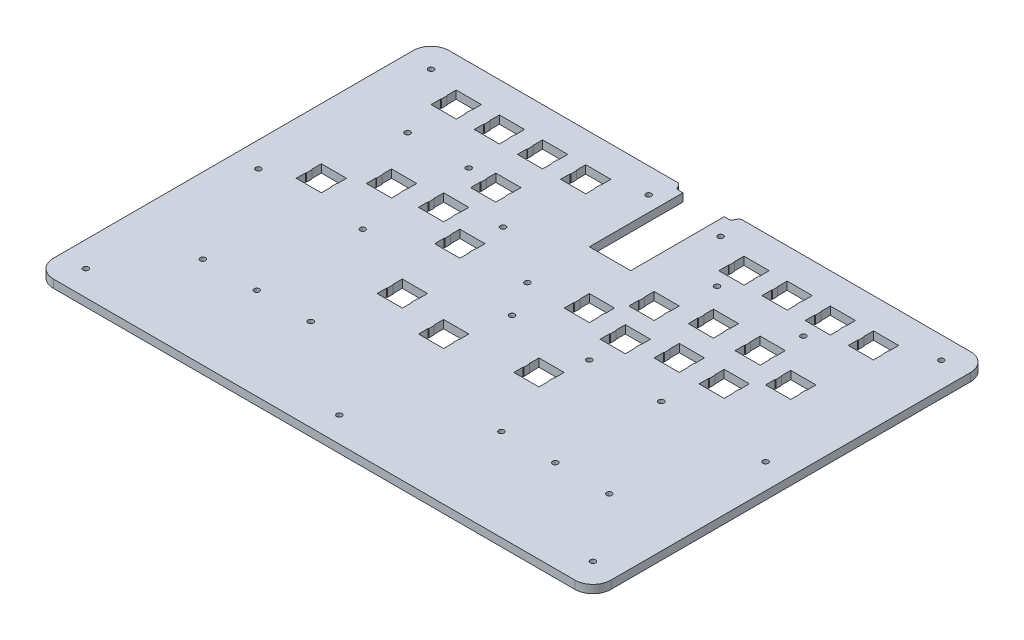
SolidWorks part; units mm, degrees
ref_plane "前视基准面" through (0, 0, 0) normal (0, 0, 1) x (1, 0, 0)
ref_plane "上视基准面" through (0, 0, 0) normal (0, 1, 0) x (1, 0, 0)
ref_plane "右视基准面" through (0, 0, 0) normal (1, 0, 0) x (0, 0, -1)
sketch "草图1" plane through (0, 0, 0) normal (0, 1, 0) x (1, 0, 0)
  line L0 (183.25, -128.5) -> (183.25, -131.5)
  line L1 (10, 0) -> (136.8844, 0)
  line L2 (0, -10) -> (0, -210)
  line L3 (10, -220) -> (300, -220)
  line L4 (310, -10) -> (310, -210)
  line L5 (28.75, -14.75) -> (47.25, -14.75) construction
  line L6 (28.75, -14.75) -> (28.75, -33.25) construction
  line L7 (28.75, -33.25) -> (47.25, -33.25) construction
  line L8 (173, -85) -> (173, 0) construction
  line L9 (173, -85) -> (310, -85) construction
  line L10 (190, -66) -> (190, 0) construction
  line L11 (215, -58) -> (215, 0) construction
  line L12 (241, -58) -> (241, 0) construction
  line L13 (247, -84) -> (247, 0) construction
  line L14 (222, -84) -> (222, 0) construction
  line L15 (0, -220) -> (310, 0) construction
  line L16 (241, -58) -> (310, -58) construction
  line L17 (247, -84) -> (310, -84) construction
  line L18 (215, -58) -> (310, -58) construction
  line L19 (222, -84) -> (310, -84) construction
  line L20 (190, -66) -> (310, -66) construction
  line L21 (310, -220) -> (0, 0) construction
  line L22 (141.1791, -3.5) -> (143.5, -3.5)
  line L23 (139.4291, -2.4682) -> (138.6344, -1.0318)
  line L24 (170.5709, -2.4682) -> (171.3656, -1.0318)
  line L25 (173.1156, 0) -> (300, 0)
  line L26 (155, -110) -> (155, -220) construction
  line L27 (47.25, -14.75) -> (47.25, -33.25) construction
  line L28 (28.75, -14.75) -> (47.25, -33.25) construction
  line L29 (28.75, -33.25) -> (47.25, -14.75) construction
  line L30 (52.75, -14.75) -> (71.25, -14.75) construction
  line L31 (52.75, -14.75) -> (52.75, -33.25) construction
  line L32 (52.75, -33.25) -> (71.25, -33.25) construction
  line L33 (71.25, -14.75) -> (71.25, -33.25) construction
  line L34 (52.75, -14.75) -> (71.25, -33.25) construction
  line L35 (52.75, -33.25) -> (71.25, -14.75) construction
  line L36 (76.75, -14.75) -> (95.25, -14.75) construction
  line L37 (76.75, -14.75) -> (76.75, -33.25) construction
  line L38 (76.75, -33.25) -> (95.25, -33.25) construction
  line L39 (95.25, -14.75) -> (95.25, -33.25) construction
  line L40 (76.75, -14.75) -> (95.25, -33.25) construction
  line L41 (76.75, -33.25) -> (95.25, -14.75) construction
  line L42 (100.75, -14.75) -> (119.25, -14.75) construction
  line L43 (100.75, -14.75) -> (100.75, -33.25) construction
  line L44 (100.75, -33.25) -> (119.25, -33.25) construction
  line L45 (119.25, -14.75) -> (119.25, -33.25) construction
  line L46 (100.75, -14.75) -> (119.25, -33.25) construction
  line L47 (100.75, -33.25) -> (119.25, -14.75) construction
  line L48 (188.75, -14.75) -> (207.25, -14.75) construction
  line L49 (188.75, -14.75) -> (188.75, -33.25) construction
  line L50 (188.75, -33.25) -> (207.25, -33.25) construction
  line L51 (207.25, -14.75) -> (207.25, -33.25) construction
  line L52 (188.75, -14.75) -> (207.25, -33.25) construction
  line L53 (188.75, -33.25) -> (207.25, -14.75) construction
  line L54 (212.75, -14.75) -> (231.25, -14.75) construction
  line L55 (212.75, -14.75) -> (212.75, -33.25) construction
  line L56 (212.75, -33.25) -> (231.25, -33.25) construction
  line L57 (231.25, -14.75) -> (231.25, -33.25) construction
  line L58 (212.75, -14.75) -> (231.25, -33.25) construction
  line L59 (212.75, -33.25) -> (231.25, -14.75) construction
  line L60 (236.75, -14.75) -> (255.25, -14.75) construction
  line L61 (236.75, -14.75) -> (236.75, -33.25) construction
  line L62 (236.75, -33.25) -> (255.25, -33.25) construction
  line L63 (255.25, -14.75) -> (255.25, -33.25) construction
  line L64 (236.75, -14.75) -> (255.25, -33.25) construction
  line L65 (236.75, -33.25) -> (255.25, -14.75) construction
  line L66 (260.75, -14.75) -> (279.25, -14.75) construction
  line L67 (260.75, -14.75) -> (260.75, -33.25) construction
  line L68 (260.75, -33.25) -> (279.25, -33.25) construction
  line L69 (279.25, -14.75) -> (279.25, -33.25) construction
  line L70 (260.75, -14.75) -> (279.25, -33.25) construction
  line L71 (260.75, -33.25) -> (279.25, -14.75) construction
  line L72 (183, -123) -> (197, -123)
  line L73 (183, -123) -> (183, -128.25)
  line L74 (183, -137) -> (197, -137)
  line L75 (197, -123) -> (197, -128.25)
  line L76 (183, -123) -> (197, -137) construction
  line L77 (183, -137) -> (197, -123) construction
  line L78 (183.25, -128.5) -> (183, -128.25)
  line L79 (183.25, -131.5) -> (183, -131.75)
  line L80 (196.75, -128.5) -> (196.75, -131.5)
  line L81 (196.75, -128.5) -> (197, -128.25)
  line L82 (196.75, -131.5) -> (197, -131.75)
  line L83 (183, -131.75) -> (183, -137)
  line L84 (197, -131.75) -> (197, -137)
  line L85 (31.25, -22.5) -> (31.25, -25.5)
  line L86 (31, -17) -> (45, -17)
  line L87 (31, -17) -> (31, -22.25)
  line L88 (31, -31) -> (45, -31)
  line L89 (45, -17) -> (45, -22.25)
  line L90 (31, -17) -> (45, -31) construction
  line L91 (31, -31) -> (45, -17) construction
  line L92 (31.25, -22.5) -> (31, -22.25)
  line L93 (31.25, -25.5) -> (31, -25.75)
  line L94 (44.75, -22.5) -> (44.75, -25.5)
  line L95 (44.75, -22.5) -> (45, -22.25)
  line L96 (44.75, -25.5) -> (45, -25.75)
  line L97 (31, -25.75) -> (31, -31)
  line L98 (45, -25.75) -> (45, -31)
  line L99 (55.25, -22.5) -> (55.25, -25.5)
  line L100 (55, -17) -> (69, -17)
  line L101 (55, -17) -> (55, -22.25)
  line L102 (55, -31) -> (69, -31)
  line L103 (69, -17) -> (69, -22.25)
  line L104 (55, -17) -> (69, -31) construction
  line L105 (55, -31) -> (69, -17) construction
  line L106 (55.25, -22.5) -> (55, -22.25)
  line L107 (55.25, -25.5) -> (55, -25.75)
  line L108 (68.75, -22.5) -> (68.75, -25.5)
  line L109 (68.75, -22.5) -> (69, -22.25)
  line L110 (68.75, -25.5) -> (69, -25.75)
  line L111 (55, -25.75) -> (55, -31)
  line L112 (69, -25.75) -> (69, -31)
  line L113 (79.25, -22.5) -> (79.25, -25.5)
  line L114 (79, -17) -> (93, -17)
  line L115 (79, -17) -> (79, -22.25)
  line L116 (79, -31) -> (93, -31)
  line L117 (93, -17) -> (93, -22.25)
  line L118 (79, -17) -> (93, -31) construction
  line L119 (79, -31) -> (93, -17) construction
  line L120 (79.25, -22.5) -> (79, -22.25)
  line L121 (79.25, -25.5) -> (79, -25.75)
  line L122 (92.75, -22.5) -> (92.75, -25.5)
  line L123 (92.75, -22.5) -> (93, -22.25)
  line L124 (92.75, -25.5) -> (93, -25.75)
  line L125 (79, -25.75) -> (79, -31)
  line L126 (93, -25.75) -> (93, -31)
  line L127 (103.25, -22.5) -> (103.25, -25.5)
  line L128 (103, -17) -> (117, -17)
  line L129 (103, -17) -> (103, -22.25)
  line L130 (103, -31) -> (117, -31)
  line L131 (117, -17) -> (117, -22.25)
  line L132 (103, -17) -> (117, -31) construction
  line L133 (103, -31) -> (117, -17) construction
  line L134 (103.25, -22.5) -> (103, -22.25)
  line L135 (103.25, -25.5) -> (103, -25.75)
  line L136 (116.75, -22.5) -> (116.75, -25.5)
  line L137 (116.75, -22.5) -> (117, -22.25)
  line L138 (116.75, -25.5) -> (117, -25.75)
  line L139 (103, -25.75) -> (103, -31)
  line L140 (117, -25.75) -> (117, -31)
  line L141 (191.25, -22.5) -> (191.25, -25.5)
  line L142 (191, -17) -> (205, -17)
  line L143 (191, -17) -> (191, -22.25)
  line L144 (191, -31) -> (205, -31)
  line L145 (205, -17) -> (205, -22.25)
  line L146 (191, -17) -> (205, -31) construction
  line L147 (191, -31) -> (205, -17) construction
  line L148 (191.25, -22.5) -> (191, -22.25)
  line L149 (191.25, -25.5) -> (191, -25.75)
  line L150 (204.75, -22.5) -> (204.75, -25.5)
  line L151 (204.75, -22.5) -> (205, -22.25)
  line L152 (204.75, -25.5) -> (205, -25.75)
  line L153 (191, -25.75) -> (191, -31)
  line L154 (205, -25.75) -> (205, -31)
  line L155 (215.25, -22.5) -> (215.25, -25.5)
  line L156 (215, -17) -> (229, -17)
  line L157 (215, -17) -> (215, -22.25)
  line L158 (215, -31) -> (229, -31)
  line L159 (229, -17) -> (229, -22.25)
  line L160 (215, -17) -> (229, -31) construction
  line L161 (215, -31) -> (229, -17) construction
  line L162 (215.25, -22.5) -> (215, -22.25)
  line L163 (215.25, -25.5) -> (215, -25.75)
  line L164 (228.75, -22.5) -> (228.75, -25.5)
  line L165 (228.75, -22.5) -> (229, -22.25)
  line L166 (228.75, -25.5) -> (229, -25.75)
  line L167 (215, -25.75) -> (215, -31)
  line L168 (229, -25.75) -> (229, -31)
  line L169 (239.25, -22.5) -> (239.25, -25.5)
  line L170 (239, -17) -> (253, -17)
  line L171 (239, -17) -> (239, -22.25)
  line L172 (239, -31) -> (253, -31)
  line L173 (253, -17) -> (253, -22.25)
  line L174 (239, -17) -> (253, -31) construction
  line L175 (239, -31) -> (253, -17) construction
  line L176 (239.25, -22.5) -> (239, -22.25)
  line L177 (239.25, -25.5) -> (239, -25.75)
  line L178 (252.75, -22.5) -> (252.75, -25.5)
  line L179 (252.75, -22.5) -> (253, -22.25)
  line L180 (252.75, -25.5) -> (253, -25.75)
  line L181 (239, -25.75) -> (239, -31)
  line L182 (253, -25.75) -> (253, -31)
  line L183 (263.25, -22.5) -> (263.25, -25.5)
  line L184 (263, -17) -> (277, -17)
  line L185 (263, -17) -> (263, -22.25)
  line L186 (263, -31) -> (277, -31)
  line L187 (277, -17) -> (277, -22.25)
  line L188 (263, -17) -> (277, -31) construction
  line L189 (263, -31) -> (277, -17) construction
  line L190 (263.25, -22.5) -> (263, -22.25)
  line L191 (263.25, -25.5) -> (263, -25.75)
  line L192 (276.75, -22.5) -> (276.75, -25.5)
  line L193 (276.75, -22.5) -> (277, -22.25)
  line L194 (276.75, -25.5) -> (277, -25.75)
  line L195 (263, -25.75) -> (263, -31)
  line L196 (277, -25.75) -> (277, -31)
  line L197 (259.25, -64.5) -> (259.25, -67.5)
  line L198 (259, -59) -> (273, -59)
  line L199 (259, -59) -> (259, -64.25)
  line L200 (259, -73) -> (273, -73)
  line L201 (273, -59) -> (273, -64.25)
  line L202 (259, -59) -> (273, -73) construction
  line L203 (259, -73) -> (273, -59) construction
  line L204 (259.25, -64.5) -> (259, -64.25)
  line L205 (259.25, -67.5) -> (259, -67.75)
  line L206 (272.75, -64.5) -> (272.75, -67.5)
  line L207 (272.75, -64.5) -> (273, -64.25)
  line L208 (272.75, -67.5) -> (273, -67.75)
  line L209 (259, -67.75) -> (259, -73)
  line L210 (273, -67.75) -> (273, -73)
  line L211 (240.25, -82.5) -> (240.25, -85.5)
  line L212 (240, -77) -> (254, -77)
  line L213 (240, -77) -> (240, -82.25)
  line L214 (240, -91) -> (254, -91)
  line L215 (254, -77) -> (254, -82.25)
  line L216 (240, -77) -> (254, -91) construction
  line L217 (240, -91) -> (254, -77) construction
  line L218 (240.25, -82.5) -> (240, -82.25)
  line L219 (240.25, -85.5) -> (240, -85.75)
  line L220 (253.75, -82.5) -> (253.75, -85.5)
  line L221 (253.75, -82.5) -> (254, -82.25)
  line L222 (253.75, -85.5) -> (254, -85.75)
  line L223 (240, -85.75) -> (240, -91)
  line L224 (254, -85.75) -> (254, -91)
  line L225 (234.25, -56.5) -> (234.25, -59.5)
  line L226 (234, -51) -> (248, -51)
  line L227 (234, -51) -> (234, -56.25)
  line L228 (234, -65) -> (248, -65)
  line L229 (248, -51) -> (248, -56.25)
  line L230 (234, -51) -> (248, -65) construction
  line L231 (234, -65) -> (248, -51) construction
  line L232 (234.25, -56.5) -> (234, -56.25)
  line L233 (234.25, -59.5) -> (234, -59.75)
  line L234 (247.75, -56.5) -> (247.75, -59.5)
  line L235 (247.75, -56.5) -> (248, -56.25)
  line L236 (247.75, -59.5) -> (248, -59.75)
  line L237 (234, -59.75) -> (234, -65)
  line L238 (248, -59.75) -> (248, -65)
  line L239 (215.25, -82.5) -> (215.25, -85.5)
  line L240 (215, -77) -> (229, -77)
  line L241 (215, -77) -> (215, -82.25)
  line L242 (215, -91) -> (229, -91)
  line L243 (229, -77) -> (229, -82.25)
  line L244 (215, -77) -> (229, -91) construction
  line L245 (215, -91) -> (229, -77) construction
  line L246 (215.25, -82.5) -> (215, -82.25)
  line L247 (215.25, -85.5) -> (215, -85.75)
  line L248 (228.75, -82.5) -> (228.75, -85.5)
  line L249 (228.75, -82.5) -> (229, -82.25)
  line L250 (228.75, -85.5) -> (229, -85.75)
  line L251 (215, -85.75) -> (215, -91)
  line L252 (229, -85.75) -> (229, -91)
  line L253 (29.25, -95.5) -> (29.25, -98.5)
  line L254 (29, -90) -> (43, -90)
  line L255 (29, -90) -> (29, -95.25)
  line L256 (29, -104) -> (43, -104)
  line L257 (43, -90) -> (43, -95.25)
  line L258 (29, -90) -> (43, -104) construction
  line L259 (29, -104) -> (43, -90) construction
  line L260 (29.25, -95.5) -> (29, -95.25)
  line L261 (29.25, -98.5) -> (29, -98.75)
  line L262 (42.75, -95.5) -> (42.75, -98.5)
  line L263 (42.75, -95.5) -> (43, -95.25)
  line L264 (42.75, -98.5) -> (43, -98.75)
  line L265 (29, -98.75) -> (29, -104)
  line L266 (43, -98.75) -> (43, -104)
  line L267 (51.25, -78.5) -> (51.25, -81.5)
  line L268 (51, -73) -> (65, -73)
  line L269 (51, -73) -> (51, -78.25)
  line L270 (51, -87) -> (65, -87)
  line L271 (65, -73) -> (65, -78.25)
  line L272 (51, -73) -> (65, -87) construction
  line L273 (51, -87) -> (65, -73) construction
  line L274 (51.25, -78.5) -> (51, -78.25)
  line L275 (51.25, -81.5) -> (51, -81.75)
  line L276 (64.75, -78.5) -> (64.75, -81.5)
  line L277 (64.75, -78.5) -> (65, -78.25)
  line L278 (64.75, -81.5) -> (65, -81.75)
  line L279 (51, -81.75) -> (51, -87)
  line L280 (65, -81.75) -> (65, -87)
  line L281 (77.25, -75.5) -> (77.25, -78.5)
  line L282 (77, -70) -> (91, -70)
  line L283 (77, -70) -> (77, -75.25)
  line L284 (77, -84) -> (91, -84)
  line L285 (91, -70) -> (91, -75.25)
  line L286 (77, -70) -> (91, -84) construction
  line L287 (77, -84) -> (91, -70) construction
  line L288 (77.25, -75.5) -> (77, -75.25)
  line L289 (77.25, -78.5) -> (77, -78.75)
  line L290 (90.75, -75.5) -> (90.75, -78.5)
  line L291 (90.75, -75.5) -> (91, -75.25)
  line L292 (90.75, -78.5) -> (91, -78.75)
  line L293 (77, -78.75) -> (77, -84)
  line L294 (91, -78.75) -> (91, -84)
  line L295 (82.25, -51.5) -> (82.25, -54.5)
  line L296 (82, -46) -> (96, -46)
  line L297 (82, -46) -> (82, -51.25)
  line L298 (82, -60) -> (96, -60)
  line L299 (96, -46) -> (96, -51.25)
  line L300 (82, -46) -> (96, -60) construction
  line L301 (82, -60) -> (96, -46) construction
  line L302 (82.25, -51.5) -> (82, -51.25)
  line L303 (82.25, -54.5) -> (82, -54.75)
  line L304 (95.75, -51.5) -> (95.75, -54.5)
  line L305 (95.75, -51.5) -> (96, -51.25)
  line L306 (95.75, -54.5) -> (96, -54.75)
  line L307 (82, -54.75) -> (82, -60)
  line L308 (96, -54.75) -> (96, -60)
  line L309 (99.25, -88.5) -> (99.25, -91.5)
  line L310 (99, -83) -> (113, -83)
  line L311 (99, -83) -> (99, -88.25)
  line L312 (99, -97) -> (113, -97)
  line L313 (113, -83) -> (113, -88.25)
  line L314 (99, -83) -> (113, -97) construction
  line L315 (99, -97) -> (113, -83) construction
  line L316 (99.25, -88.5) -> (99, -88.25)
  line L317 (99.25, -91.5) -> (99, -91.75)
  line L318 (112.75, -88.5) -> (112.75, -91.5)
  line L319 (112.75, -88.5) -> (113, -88.25)
  line L320 (112.75, -91.5) -> (113, -91.75)
  line L321 (99, -91.75) -> (99, -97)
  line L322 (113, -91.75) -> (113, -97)
  line L323 (208.25, -56.5) -> (208.25, -59.5)
  line L324 (208, -51) -> (222, -51)
  line L325 (208, -51) -> (208, -56.25)
  line L326 (208, -65) -> (222, -65)
  line L327 (222, -51) -> (222, -56.25)
  line L328 (208, -51) -> (222, -65) construction
  line L329 (208, -65) -> (222, -51) construction
  line L330 (208.25, -56.5) -> (208, -56.25)
  line L331 (208.25, -59.5) -> (208, -59.75)
  line L332 (221.75, -56.5) -> (221.75, -59.5)
  line L333 (221.75, -56.5) -> (222, -56.25)
  line L334 (221.75, -59.5) -> (222, -59.75)
  line L335 (208, -59.75) -> (208, -65)
  line L336 (222, -59.75) -> (222, -65)
  line L337 (183.25, -64.5) -> (183.25, -67.5)
  line L338 (183, -59) -> (197, -59)
  line L339 (183, -59) -> (183, -64.25)
  line L340 (183, -73) -> (197, -73)
  line L341 (197, -59) -> (197, -64.25)
  line L342 (183, -59) -> (197, -73) construction
  line L343 (183, -73) -> (197, -59) construction
  line L344 (183.25, -64.5) -> (183, -64.25)
  line L345 (183.25, -67.5) -> (183, -67.75)
  line L346 (196.75, -64.5) -> (196.75, -67.5)
  line L347 (196.75, -64.5) -> (197, -64.25)
  line L348 (196.75, -67.5) -> (197, -67.75)
  line L349 (183, -67.75) -> (183, -73)
  line L350 (197, -67.75) -> (197, -73)
  line L351 (191.25, -88.5) -> (191.25, -91.5)
  line L352 (191, -83) -> (205, -83)
  line L353 (191, -83) -> (191, -88.25)
  line L354 (191, -97) -> (205, -97)
  line L355 (205, -83) -> (205, -88.25)
  line L356 (191, -83) -> (205, -97) construction
  line L357 (191, -97) -> (205, -83) construction
  line L358 (191.25, -88.5) -> (191, -88.25)
  line L359 (191.25, -91.5) -> (191, -91.75)
  line L360 (204.75, -88.5) -> (204.75, -91.5)
  line L361 (204.75, -88.5) -> (205, -88.25)
  line L362 (204.75, -91.5) -> (205, -91.75)
  line L363 (191, -91.75) -> (191, -97)
  line L364 (205, -91.75) -> (205, -97)
  line L365 (166.25, -83.5) -> (166.25, -86.5)
  line L366 (166, -78) -> (180, -78)
  line L367 (166, -78) -> (166, -83.25)
  line L368 (166, -92) -> (180, -92)
  line L369 (180, -78) -> (180, -83.25)
  line L370 (166, -78) -> (180, -92) construction
  line L371 (166, -92) -> (180, -78) construction
  line L372 (166.25, -83.5) -> (166, -83.25)
  line L373 (166.25, -86.5) -> (166, -86.75)
  line L374 (179.75, -83.5) -> (179.75, -86.5)
  line L375 (179.75, -83.5) -> (180, -83.25)
  line L376 (179.75, -86.5) -> (180, -86.75)
  line L377 (166, -86.75) -> (166, -92)
  line L378 (180, -86.75) -> (180, -92)
  line L379 (107.25, -128.5) -> (107.25, -131.5)
  line L380 (107, -123) -> (121, -123)
  line L381 (107, -123) -> (107, -128.25)
  line L382 (107, -137) -> (121, -137)
  line L383 (121, -123) -> (121, -128.25)
  line L384 (107, -123) -> (121, -137) construction
  line L385 (107, -137) -> (121, -123) construction
  line L386 (107.25, -128.5) -> (107, -128.25)
  line L387 (107.25, -131.5) -> (107, -131.75)
  line L388 (120.75, -128.5) -> (120.75, -131.5)
  line L389 (120.75, -128.5) -> (121, -128.25)
  line L390 (120.75, -131.5) -> (121, -131.75)
  line L391 (107, -131.75) -> (107, -137)
  line L392 (121, -131.75) -> (121, -137)
  line L393 (138.25, -136.5) -> (138.25, -139.5)
  line L394 (138, -131) -> (152, -131)
  line L395 (138, -131) -> (138, -136.25)
  line L396 (138, -145) -> (152, -145)
  line L397 (152, -131) -> (152, -136.25)
  line L398 (138, -131) -> (152, -145) construction
  line L399 (138, -145) -> (152, -131) construction
  line L400 (138.25, -136.5) -> (138, -136.25)
  line L401 (138.25, -139.5) -> (138, -139.75)
  line L402 (151.75, -136.5) -> (151.75, -139.5)
  line L403 (151.75, -136.5) -> (152, -136.25)
  line L404 (151.75, -139.5) -> (152, -139.75)
  line L405 (138, -139.75) -> (138, -145)
  line L406 (152, -139.75) -> (152, -145)
  line L407 (166.5, -3.5) -> (168.8209, -3.5)
  line L409 (143.5, -3.5) -> (143.5, -55.5)
  line L410 (143.5, -55.5) -> (166.5, -55.5)
  line L411 (166.5, -3.5) -> (166.5, -55.5)
  line L412 (143.5, -3.5) -> (166.5, -55.5) construction
  line L413 (143.5, -55.5) -> (166.5, -3.5) construction
  arc A0 (10, 0) -> (0, -10) centre (10, -10) ccw
  arc A1 (0, -210) -> (10, -220) centre (10, -210) ccw
  arc A2 (300, -220) -> (310, -210) centre (300, -210) ccw
  arc A3 (300, 0) -> (310, -10) centre (300, -10) cw
  circle A8 centre (173, -85) radius 11 construction
  circle A9 centre (190, -66) radius 11 construction
  circle A11 centre (215, -58) radius 11 construction
  circle A12 centre (222, -84) radius 11 construction
  circle A13 centre (247, -84) radius 11 construction
  circle A14 centre (241, -58) radius 11 construction
  circle A15 centre (14, -14) radius 1.5
  circle A16 centre (14, -206) radius 1.5
  circle A17 centre (296, -206) radius 1.5
  circle A18 centre (296, -12.2857) radius 1.5
  arc A19 (173.1156, 0) -> (171.3656, -1.0318) centre (173.1156, -2) ccw
  arc A20 (170.5709, -2.4682) -> (168.8209, -3.5) centre (168.8209, -1.5) cw
  arc A21 (141.1791, -3.5) -> (139.4291, -2.4682) centre (141.1791, -1.5) cw
  arc A22 (136.8844, 0) -> (138.6344, -1.0318) centre (136.8844, -2) cw
  circle A24 centre (198, -90) radius 11 construction
  circle A25 centre (114, -130) radius 13.5 construction
  circle A26 centre (190, -130) radius 13.5 construction
  circle A27 centre (155, -206) radius 1.5
  circle A28 centre (175, -14) radius 1.5
  circle A29 centre (145, -138) radius 11 construction
  circle A30 centre (106, -90) radius 11 construction
  circle A31 centre (84, -77) radius 11 construction
  circle A32 centre (58, -80) radius 11 construction
  circle A33 centre (36, -97) radius 11 construction
  circle A34 centre (89, -53) radius 11 construction
  circle A35 centre (266, -66) radius 11 construction
  circle A36 centre (110, -24) radius 4.5 construction
  circle A37 centre (86, -24) radius 4.5 construction
  circle A38 centre (62, -24) radius 4.5 construction
  circle A39 centre (38, -24) radius 4.5 construction
  circle A40 centre (198, -24) radius 4.5 construction
  circle A41 centre (222, -24) radius 4.5 construction
  circle A42 centre (246, -24) radius 4.5 construction
  circle A43 centre (270, -24) radius 4.5 construction
  circle A48 centre (135, -14) radius 1.5
  circle A51 centre (296, -110) radius 1.5
  circle A52 centre (14, -110) radius 1.5
  circle A53 centre (155, -110) radius 1.5
  circle A54 centre (72, -110) radius 1.5
  circle A55 centre (72, -168.9032) radius 1.5
  circle A56 centre (72, -51.0968) radius 1.5
  circle A57 centre (42, -168.9032) radius 1.5
  circle A58 centre (102, -168.9032) radius 1.5
  circle A59 centre (238, -110) radius 1.5
  circle A60 centre (238, -168.9032) radius 1.5
  circle A61 centre (268, -168.9032) radius 1.5
  circle A62 centre (208, -168.9032) radius 1.5
  circle A63 centre (246, -39) radius 1.5
  circle A64 centre (198, -39) radius 1.5
  circle A65 centre (110, -70) radius 1.5
  circle A66 centre (38, -51.0968) radius 1.5
  circle A67 centre (198, -110) radius 1.5
  circle A68 centre (143.5, -90) radius 1.5
  point P8 (0, 0)
  point P12 (0, -220)
  point P15 (310, -220)
  point P18 (310, 0)
  point P70 (171.9365, 0)
  point P73 (170, -3.5)
  point P76 (140, -3.5)
  point P79 (138.0635, 0)
  point P147 (190, -130)
  point P152 (155, -29.5)
  point P155 (183.25, -130)
  point P160 (196.75, -130)
  point P163 (38, -24)
  point P170 (31.25, -24)
  point P175 (44.75, -24)
  point P180 (62, -24)
  point P187 (55.25, -24)
  point P192 (68.75, -24)
  point P196 (86, -24)
  point P203 (79.25, -24)
  point P208 (92.75, -24)
  point P213 (110, -24)
  point P220 (103.25, -24)
  point P225 (116.75, -24)
  point P229 (198, -24)
  point P236 (191.25, -24)
  point P241 (204.75, -24)
  point P245 (222, -24)
  point P252 (215.25, -24)
  point P257 (228.75, -24)
  point P261 (246, -24)
  point P268 (239.25, -24)
  point P273 (252.75, -24)
  point P277 (270, -24)
  point P284 (263.25, -24)
  point P289 (276.75, -24)
  point P293 (266, -66)
  point P300 (259.25, -66)
  point P305 (272.75, -66)
  point P310 (247, -84)
  point P317 (240.25, -84)
  point P322 (253.75, -84)
  point P326 (241, -58)
  point P333 (234.25, -58)
  point P338 (247.75, -58)
  point P342 (222, -84)
  point P349 (215.25, -84)
  point P354 (228.75, -84)
  point P358 (36, -97)
  point P365 (29.25, -97)
  point P370 (42.75, -97)
  point P374 (58, -80)
  point P381 (51.25, -80)
  point P386 (64.75, -80)
  point P390 (84, -77)
  point P397 (77.25, -77)
  point P402 (90.75, -77)
  point P407 (89, -53)
  point P414 (82.25, -53)
  point P419 (95.75, -53)
  point P423 (106, -90)
  point P430 (99.25, -90)
  point P435 (112.75, -90)
  point P439 (215, -58)
  point P446 (208.25, -58)
  point P451 (221.75, -58)
  point P455 (190, -66)
  point P462 (183.25, -66)
  point P467 (196.75, -66)
  point P471 (198, -90)
  point P478 (191.25, -90)
  point P483 (204.75, -90)
  point P492 (173, -85)
  point P499 (166.25, -85)
  point P504 (179.75, -85)
  point P508 (114, -130)
  point P515 (107.25, -130)
  point P520 (120.75, -130)
  point P524 (145, -138)
  point P531 (138.25, -138)
  point P536 (151.75, -138)
  dimension "D3" = 10
  dimension "D7" = 90
  dimension "D10" = 22
  dimension "D15" = 53
  dimension "D16" = 22
  dimension "D19" = 22
  dimension "D20" = 22
  dimension "D21" = 22
  dimension "D22" = 84
  dimension "D23" = 22
  dimension "D24" = 22
  dimension "D32" = 22
  dimension "D34" = 3
  dimension "D37" = 3
  dimension "D40" = 3
  dimension "D43" = 3
  dimension "D47" = 3.5
  dimension "D50" = 140
  dimension "D51" = 2
  dimension "D52" = 90
  dimension "D54" = 27
  dimension "D56" = 27
  dimension "D59" = 3
  dimension "D61" = 14
  dimension "D62" = 3
  dimension "D64" = 22
  dimension "D8" = 22
  dimension "D9" = 22
  dimension "D11" = 22
  dimension "D12" = 22
  dimension "D13" = 22
  dimension "D76" = 9
  dimension "D84" = 9
  dimension "D86" = 3
  dimension "D89" = 18.5
  dimension "D92" = 18.5
  dimension "D95" = 18.5
  dimension "D98" = 3
  dimension "D101" = 18.5
  dimension "D103" = 18.5
  dimension "D87" = 3
  dimension "D301" = 3
  dimension "D302" = 3
  dimension "D304" = 3
  dimension "D305" = 3
  dimension "D306" = 3
  dimension "D308" = 3
  dimension "D310" = 3
  dimension "D312" = 3
  dimension "D313" = 3
  dimension "D314" = 3
  dimension "D317" = 3
  dimension "D319" = 3
  dimension "D321" = 3
  dimension "D323" = 3
  dimension "D324" = 3
  dimension "D325" = 3
  dimension "D1" = 220
  dimension "D2" = 310
  dimension "D14" = 89
  dimension "D17" = 85
  dimension "D18" = 137
  dimension "D25" = 66
  dimension "D26" = 120
  dimension "D27" = 36
  dimension "D28" = 58
  dimension "D29" = 95
  dimension "D30" = 88
  dimension "D31" = 69
  dimension "D33" = 63
  dimension "D35" = 14
  dimension "D36" = 14
  dimension "D38" = 14
  dimension "D39" = 14
  dimension "D41" = 14
  dimension "D42" = 14
  dimension "D44" = 14
  dimension "D45" = 12.2857
  dimension "D46" = 4
  dimension "D48" = 30
  dimension "D49" = 4
  dimension "D53" = 112
  dimension "D55" = 114
  dimension "D57" = 90
  dimension "D58" = 120
  dimension "D60" = 14
  dimension "D63" = 135
  dimension "D65" = 82
  dimension "D66" = 145
  dimension "D67" = 97
  dimension "D68" = 80
  dimension "D69" = 58
  dimension "D70" = 84
  dimension "D71" = 77
  dimension "D72" = 90
  dimension "D73" = 106
  dimension "D74" = 44
  dimension "D75" = 66
  dimension "D78" = 24
  dimension "D79" = 110
  dimension "D80" = 24
  dimension "D82" = 24
  dimension "D83" = 24
  dimension "D85" = 40
  dimension "D88" = 18.5
  dimension "D90" = 18.5
  dimension "D91" = 18.5
  dimension "D93" = 18.5
  dimension "D94" = 18.5
  dimension "D96" = 18.5
  dimension "D97" = 18.5
  dimension "D99" = 14
  dimension "D100" = 135
  dimension "D102" = 18.5
  dimension "D104" = 18.5
  dimension "D105" = 18.5
  dimension "D106" = 18.5
  dimension "D107" = 14
  dimension "D108" = 14
  dimension "D109" = 0.25
  dimension "D110" = 3
  dimension "D111" = 135
  dimension "D112" = 3
  dimension "D113" = 0.25
  dimension "D114" = 135
  dimension "D115" = 14
  dimension "D116" = 14
  dimension "D117" = 0.25
  dimension "D118" = 3
  dimension "D119" = 135
  dimension "D120" = 3
  dimension "D121" = 0.25
  dimension "D122" = 135
  dimension "D123" = 14
  dimension "D124" = 14
  dimension "D125" = 0.25
  dimension "D126" = 3
  dimension "D127" = 135
  dimension "D128" = 3
  dimension "D129" = 0.25
  dimension "D130" = 135
  dimension "D131" = 14
  dimension "D132" = 14
  dimension "D133" = 0.25
  dimension "D134" = 3
  dimension "D135" = 135
  dimension "D136" = 3
  dimension "D137" = 0.25
  dimension "D138" = 135
  dimension "D139" = 14
  dimension "D140" = 14
  dimension "D141" = 0.25
  dimension "D142" = 3
  dimension "D143" = 135
  dimension "D144" = 3
  dimension "D145" = 0.25
  dimension "D146" = 135
  dimension "D147" = 14
  dimension "D148" = 14
  dimension "D149" = 0.25
  dimension "D150" = 3
  dimension "D151" = 135
  dimension "D152" = 3
  dimension "D153" = 0.25
  dimension "D154" = 135
  dimension "D155" = 14
  dimension "D156" = 14
  dimension "D157" = 0.25
  dimension "D158" = 3
  dimension "D159" = 135
  dimension "D160" = 3
  dimension "D161" = 0.25
  dimension "D162" = 135
  dimension "D163" = 14
  dimension "D164" = 14
  dimension "D165" = 0.25
  dimension "D166" = 3
  dimension "D167" = 135
  dimension "D168" = 3
  dimension "D169" = 0.25
  dimension "D170" = 135
  dimension "D171" = 14
  dimension "D172" = 14
  dimension "D173" = 0.25
  dimension "D174" = 3
  dimension "D175" = 135
  dimension "D176" = 3
  dimension "D177" = 0.25
  dimension "D178" = 135
  dimension "D179" = 14
  dimension "D180" = 14
  dimension "D181" = 0.25
  dimension "D182" = 3
  dimension "D183" = 135
  dimension "D184" = 3
  dimension "D185" = 0.25
  dimension "D186" = 135
  dimension "D187" = 14
  dimension "D188" = 14
  dimension "D189" = 0.25
  dimension "D190" = 3
  dimension "D191" = 135
  dimension "D192" = 3
  dimension "D193" = 0.25
  dimension "D194" = 135
  dimension "D195" = 14
  dimension "D196" = 14
  dimension "D197" = 0.25
  dimension "D198" = 3
  dimension "D199" = 135
  dimension "D200" = 3
  dimension "D201" = 0.25
  dimension "D202" = 135
  dimension "D203" = 14
  dimension "D204" = 14
  dimension "D205" = 0.25
  dimension "D206" = 3
  dimension "D207" = 135
  dimension "D208" = 3
  dimension "D209" = 0.25
  dimension "D210" = 135
  dimension "D211" = 14
  dimension "D212" = 14
  dimension "D213" = 0.25
  dimension "D214" = 3
  dimension "D215" = 135
  dimension "D216" = 3
  dimension "D217" = 0.25
  dimension "D218" = 135
  dimension "D219" = 14
  dimension "D220" = 14
  dimension "D221" = 0.25
  dimension "D222" = 3
  dimension "D223" = 135
  dimension "D224" = 3
  dimension "D225" = 0.25
  dimension "D226" = 135
  dimension "D227" = 14
  dimension "D228" = 14
  dimension "D229" = 0.25
  dimension "D230" = 3
  dimension "D231" = 135
  dimension "D232" = 3
  dimension "D233" = 0.25
  dimension "D234" = 135
  dimension "D235" = 14
  dimension "D236" = 14
  dimension "D237" = 0.25
  dimension "D238" = 3
  dimension "D239" = 135
  dimension "D240" = 3
  dimension "D241" = 0.25
  dimension "D242" = 135
  dimension "D243" = 14
  dimension "D244" = 14
  dimension "D245" = 0.25
  dimension "D246" = 3
  dimension "D247" = 135
  dimension "D248" = 3
  dimension "D249" = 0.25
  dimension "D250" = 135
  dimension "D251" = 14
  dimension "D252" = 14
  dimension "D253" = 0.25
  dimension "D254" = 3
  dimension "D255" = 135
  dimension "D256" = 3
  dimension "D257" = 0.25
  dimension "D258" = 135
  dimension "D259" = 14
  dimension "D260" = 14
  dimension "D261" = 0.25
  dimension "D262" = 3
  dimension "D263" = 135
  dimension "D264" = 3
  dimension "D265" = 0.25
  dimension "D266" = 135
  dimension "D267" = 14
  dimension "D268" = 14
  dimension "D269" = 0.25
  dimension "D270" = 3
  dimension "D271" = 135
  dimension "D272" = 3
  dimension "D273" = 0.25
  dimension "D274" = 135
  dimension "D275" = 14
  dimension "D276" = 14
  dimension "D277" = 0.25
  dimension "D278" = 3
  dimension "D279" = 135
  dimension "D280" = 3
  dimension "D281" = 0.25
  dimension "D282" = 135
  dimension "D283" = 14
  dimension "D284" = 14
  dimension "D285" = 0.25
  dimension "D286" = 3
  dimension "D287" = 135
  dimension "D288" = 3
  dimension "D289" = 0.25
  dimension "D290" = 135
  dimension "D291" = 14
  dimension "D292" = 14
  dimension "D293" = 0.25
  dimension "D294" = 3
  dimension "D295" = 135
  dimension "D296" = 3
  dimension "D297" = 0.25
  dimension "D298" = 135
  dimension "D299" = 23
  dimension "D300" = 52
  dimension "D303" = 72
  dimension "D307" = 30
  dimension "D309" = 30
  dimension "D311" = 72
  dimension "D315" = 30
  dimension "D316" = 30
  dimension "D318" = 15
  dimension "D320" = 15
  dimension "D322" = 46
  dimension "D77" = 4
  dimension "D81" = 4
extrude "凸台-拉伸1" add sketch "草图1" along normal blind 4.5
